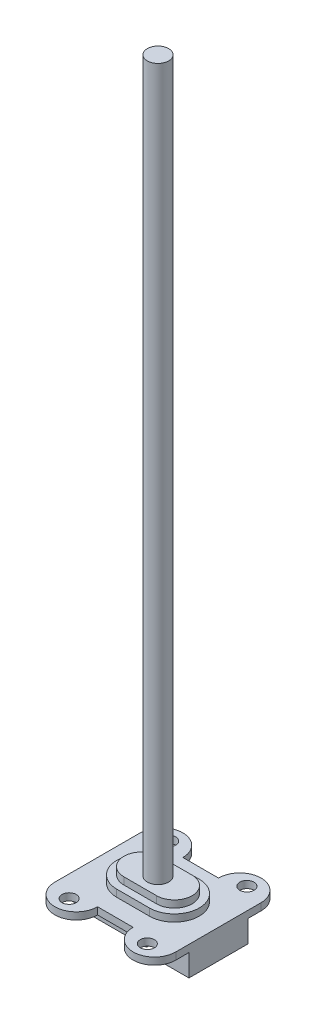
SolidWorks part; units mm, degrees
ref_plane "前视基准面" through (0, 0, 0) normal (0, 0, 1) x (1, 0, 0)
ref_plane "上视基准面" through (0, 0, 0) normal (0, 1, 0) x (1, 0, 0)
ref_plane "右视基准面" through (0, 0, 0) normal (1, 0, 0) x (0, 0, -1)
other "Configuration Table"
sketch "草图1" plane through (0, 0, 0) normal (0, 1, 0) x (1, 0, 0)
  line L1 (8.5, -9) -> (-8.5, -9)
  line L2 (8.5, -9) -> (8.5, 9)
  line L3 (8.5, 9) -> (-8.5, 9)
  line L4 (-8.5, -9) -> (-8.5, 9)
  line L5 (8.5, -9) -> (-8.5, 9) construction
  line L6 (8.5, 9) -> (-8.5, -9) construction
  point P0 (0, 0)
  dimension "D1" = 18
  dimension "D2" = 17
extrude "凸台-拉伸1" add sketch "草图1" along normal blind 1
sketch "草图2" plane through (0, 1, 0) normal (0, 1, 0) x (1, 0, 0)
  line L1 (5.5, -7) -> (-5.5, -7) construction
  line L2 (5.5, -7) -> (5.5, 7) construction
  line L3 (5.5, 7) -> (-5.5, 7) construction
  line L4 (-5.5, -7) -> (-5.5, 7) construction
  line L5 (5.5, -7) -> (-5.5, 7) construction
  line L6 (5.5, 7) -> (-5.5, -7) construction
  circle A0 centre (-5.5, 7) radius 1
  circle A1 centre (5.5, 7) radius 1
  circle A2 centre (-5.5, -7) radius 1
  circle A3 centre (5.5, -7) radius 1
  point P0 (0, 0)
  dimension "D1" = 14
  dimension "D2" = 11
extrude "切除-拉伸1" cut sketch "草图2" against normal through all
sketch "草图3" plane through (0, 1, 0) normal (0, 1, 0) x (1, 0, 0)
  line L0 (8.5, 9) -> (-8.5, 9) construction
  line L1 (-8.5, 6) -> (-8.5, 9)
  line L2 (-8.5, 9) -> (-2.5, 9)
  line L3 (-2.5, 9) -> (-2.5, 6)
  arc A0 (-2.5, 6) -> (-8.5, 6) centre (-5.5, 6) ccw
  line M10 (-8.5, 9) -> (-8.5, -9)
  line M13 (8.5, 9) -> (-8.5, 9)
extrude "切除-拉伸2" cut sketch "草图3" against normal through all contours A0 L2 M10 | A0 L3 M13
mirror "镜向1" about plane through (0, 0, 0) normal (0, 0, 1) of "切除-拉伸2"
mirror "镜向2" about plane through (0, 0, 0) normal (1, 0, 0) of "镜向1", "切除-拉伸2"
sketch "草图4" plane through (0, 1, 0) normal (0, 1, 0) x (1, 0, 0)
  line L0 (-2.5, 6) -> (2.5, 6)
  line L1 (2.5, 6) -> (2.5, 9)
  line L2 (2.5, 9) -> (2.5, 6) construction
  line L3 (2.5, 9) -> (-2.5, 9)
  line L4 (-2.5, 9) -> (-2.5, 6)
extrude "切除-拉伸3" cut sketch "草图4" against normal through all
mirror "镜向3" about plane through (0, 0, 0) normal (0, 0, 1) of "切除-拉伸3"
sketch "草图5" plane through (0, 1, 0) normal (0, 1, 0) x (1, 0, 0)
  line L0 (-2.3, 3.5) -> (2.3, 3.5)
  line L1 (2.3, -3.5) -> (-2.3, -3.5)
  line L2 (-2.3, 3.5) -> (2.3, -3.5)
  line L3 (2.3, 3.5) -> (-2.3, -3.5)
  arc A0 (-2.3, 3.5) -> (-2.3, -3.5) centre (-2.3, 0) ccw
  arc A1 (2.3, -3.5) -> (2.3, 3.5) centre (2.3, 0) ccw
  point P1 (0, 0)
  dimension "D1" = 4.6
extrude "凸台-拉伸2" add sketch "草图5" along normal blind 1 contours L2 A0 L3 | L3 L0 L2 | L2 L3 L1 | L2 A1 L3
sketch "草图6" plane through (0, 2, 0) normal (0, 1, 0) x (1, 0, 0)
  line L0 (-2.3, 2.5) -> (2.3, 2.5)
  line L1 (2.3, -2.5) -> (-2.3, -2.5)
  line L2 (-2.3, 2.5) -> (2.3, -2.5)
  line L3 (2.3, 2.5) -> (-2.3, -2.5)
  arc A0 (-2.3, 2.5) -> (-2.3, -2.5) centre (-2.3, 0) ccw
  arc A1 (2.3, -2.5) -> (2.3, 2.5) centre (2.3, 0) ccw
  point P1 (0, 0)
  dimension "D1" = 4.6
extrude "凸台-拉伸3" add sketch "草图6" along normal blind 1 contours L2 A0 L3 | L3 L0 L2 | L2 L3 L1 | L2 A1 L3
sketch "草图8" plane through (0, 0, 0) normal (1, 0, 0) x (0, 0, -1)
  line L1 (-4.15, -3.1) -> (4.15, -3.1)
  line L2 (-4.15, -3.1) -> (-4.15, 0)
  line L3 (-4.15, 0) -> (4.15, 0)
  line L4 (4.15, -3.1) -> (4.15, 0)
  line L5 (-4.15, -3.1) -> (4.15, 0) construction
  line L6 (-4.15, 0) -> (4.15, -3.1) construction
  line L8 (-6, 0) -> (6, 0) construction
  point P0 (-7.6658, 0)
  dimension "D1" = 3.1
  dimension "D2" = 8.3
  dimension "D3" = 4.15
extrude "凸台-拉伸4" add sketch "草图8" against normal blind 4.2 from surface at 8.5 starting at face at (8.5, 0.5, 0)
sketch "草图9" plane through (0, 0, 0) normal (0, -1, 0) x (1, 0, 0)
  line L1 (2.8836, -4.5) -> (-7.3164, -4.5)
  line L2 (2.8836, -4.5) -> (2.8836, 4.5)
  line L3 (2.8836, 4.5) -> (-7.3164, 4.5)
  line L4 (-7.3164, -4.5) -> (-7.3164, 4.5)
  line L5 (2.8836, -4.5) -> (-7.3164, 4.5) construction
  line L6 (2.8836, 4.5) -> (-7.3164, -4.5) construction
  point P0 (-2.2164, 0)
  dimension "D1" = 10.2
  dimension "D2" = 9
  dimension "D3" = 4.5
extrude "凸台-拉伸5" add sketch "草图9" along normal blind 2 contours L2 L1 L4 L3
sketch "草图10" plane through (0, 3, 0) normal (0, 1, 0) x (1, 0, 0)
  circle A0 centre (0, 0) radius 1.5
extrude "凸台-拉伸10" add sketch "草图10" along normal blind 100
